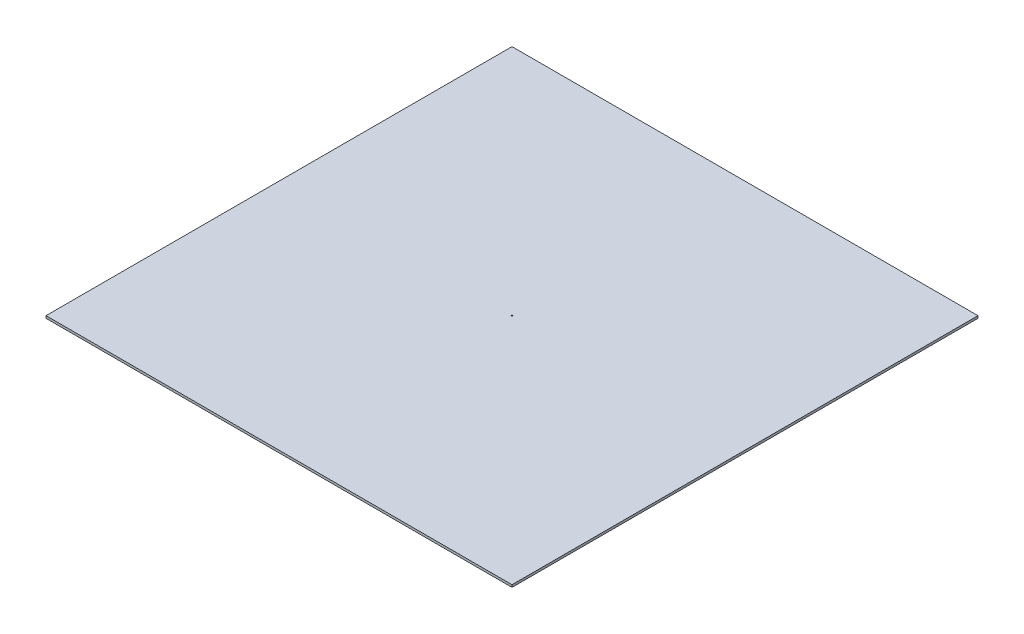
SolidWorks part; units mm, degrees
ref_plane "Front Plane" through (0, 0, 0) normal (0, 0, 1) x (1, 0, 0)
ref_plane "Top Plane" through (0, 0, 0) normal (0, 1, 0) x (1, 0, 0)
ref_plane "Right Plane" through (0, 0, 0) normal (1, 0, 0) x (0, 0, -1)
sketch "Sketch1" plane through (0, 0, 0) normal (0, 1, 0) x (1, 0, 0)
  line L1 (1000, -1000) -> (-1000, -1000)
  line L2 (1000, -1000) -> (1000, 1000)
  line L3 (1000, 1000) -> (-1000, 1000)
  line L4 (-1000, -1000) -> (-1000, 1000)
  line L5 (1000, -1000) -> (-1000, 1000) construction
  line L6 (1000, 1000) -> (-1000, -1000) construction
  circle A0 centre (0, 0) radius 2.5
  point P0 (0, 0)
  dimension "D3" = 5
  dimension "D1" = 2000
  dimension "D2" = 2000
extrude "Boss-Extrude1" add sketch "Sketch1" along normal blind 10
